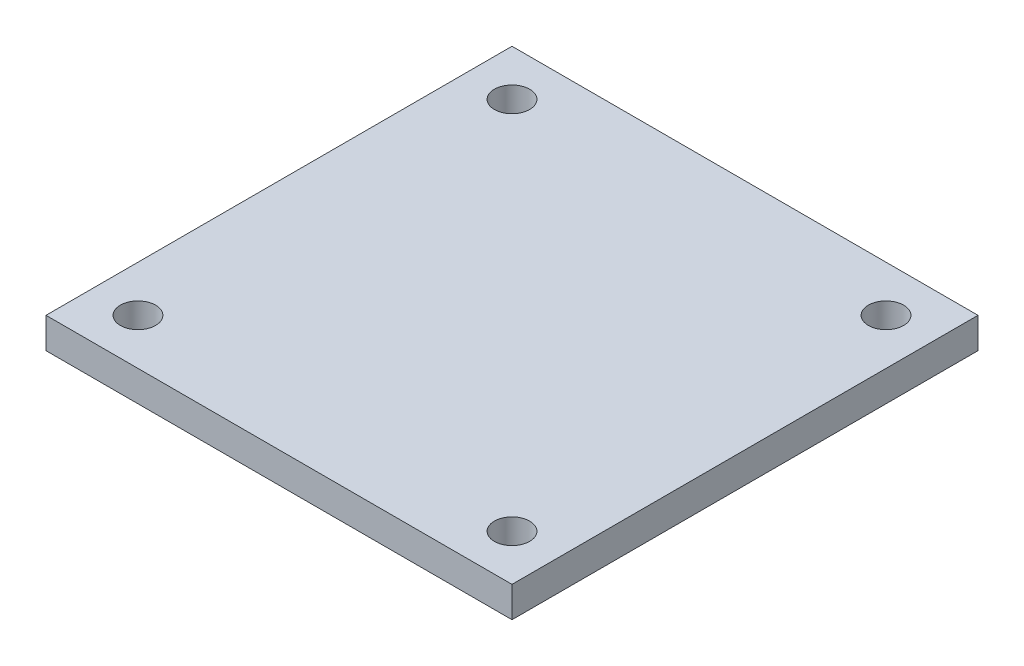
SolidWorks part; units mm, degrees
ref_plane "Front Plane" through (0, 0, 0) normal (0, 0, 1) x (1, 0, 0)
ref_plane "Top Plane" through (0, 0, 0) normal (0, 1, 0) x (1, 0, 0)
ref_plane "Right Plane" through (0, 0, 0) normal (1, 0, 0) x (0, 0, -1)
sketch "Sketch1" plane through (0, 0, 0) normal (0, 1, 0) x (1, 0, 0)
  line L0 (0, 20.3694) -> (0, -18.5901) construction
  line L1 (-15.2, 15.2) -> (15.2, 15.2)
  line L2 (-15.2, 15.2) -> (-15.2, -15.2)
  line L3 (-15.2, -15.2) -> (15.2, -15.2)
  line L4 (15.2, 15.2) -> (15.2, -15.2)
  line L5 (-15.2, 15.2) -> (15.2, -15.2) construction
  line L6 (-15.2, -15.2) -> (15.2, 15.2) construction
  line L7 (-23.468, 0) -> (25.454, 0) construction
  circle A0 centre (-12.2, 12.2) radius 1.15
  circle A1 centre (12.2, 12.2) radius 1.15
  circle A2 centre (12.2, -12.2) radius 1.15
  circle A3 centre (-12.2, -12.2) radius 1.15
  point P0 (0, 0)
  dimension "D3" = 3
  dimension "D4" = 2.3
  dimension "D5" = 3
  dimension "D1" = 30.4
  dimension "D2" = 30.4
extrude "Boss-Extrude1" add sketch "Sketch1" along normal blind 2
